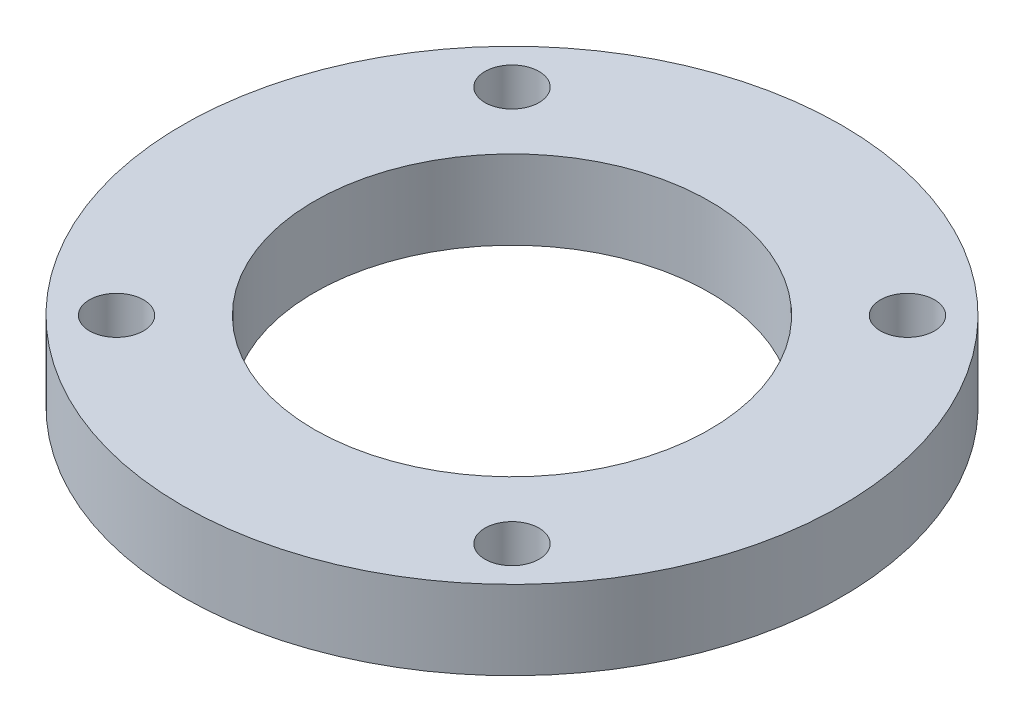
SolidWorks part; units mm, degrees
material "1060 合金"
ref_plane "前视基准面" through (0, 0, 0) normal (0, 0, 1) x (1, 0, 0)
ref_plane "上视基准面" through (0, 0, 0) normal (0, 1, 0) x (1, 0, 0)
ref_plane "右视基准面" through (0, 0, 0) normal (1, 0, 0) x (0, 0, -1)
sketch "草图1" plane through (0, 0, 0) normal (0, 1, 0) x (1, 0, 0)
  line L1 (-15, -15) -> (15, -15) construction
  line L2 (-15, -15) -> (-15, 15) construction
  line L3 (-15, 15) -> (15, 15) construction
  line L4 (15, -15) -> (15, 15) construction
  circle A0 centre (0, 0) radius 25
  circle A1 centre (-15, 15) radius 2.05
  circle A2 centre (15, 15) radius 2.05
  circle A3 centre (15, -15) radius 2.05
  circle A4 centre (-15, -15) radius 2.05
  dimension "D3" = 15
  dimension "D4" = 50
  dimension "D5" = 4.1
  dimension "D1" = 30
  dimension "D2" = 15
extrude "凸台-拉伸1" add sketch "草图1" along normal blind 6
sketch "草图2" plane through (0, 6, 0) normal (0, 1, 0) x (1, 0, 0)
  circle A0 centre (0, 0) radius 15
  dimension "D1" = 30
extrude "切除-拉伸1" cut sketch "草图2" against normal through all
